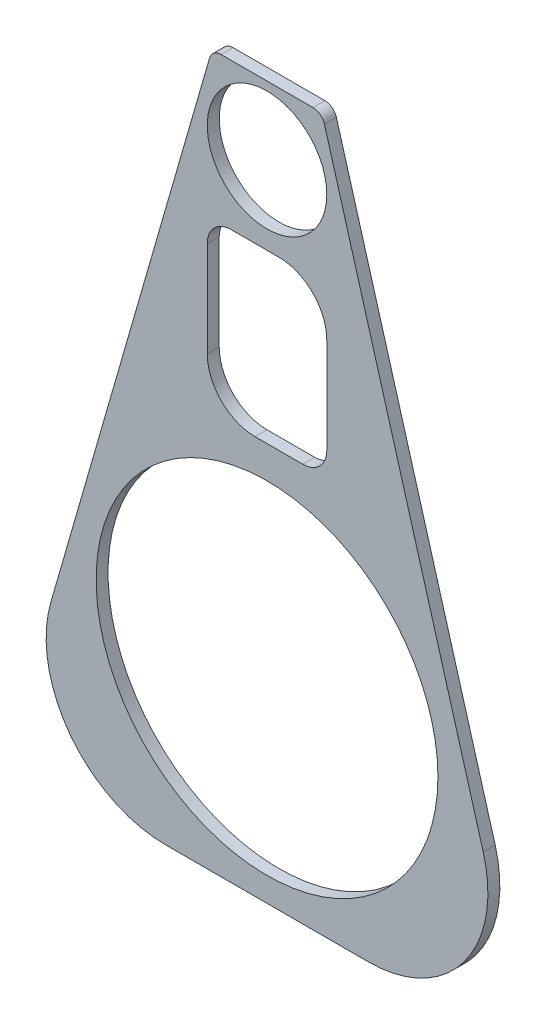
SolidWorks part; units mm, degrees
material "6061 Alloy"
ref_plane "Front" through (0, 0, 0) normal (0, 0, 1) x (1, 0, 0)
ref_plane "Top" through (0, 0, 0) normal (0, 1, 0) x (1, 0, 0)
ref_plane "Right" through (0, 0, 0) normal (1, 0, 0) x (0, 0, -1)
sketch "Sketch3" plane through (0, 0, 0) normal (0, 0, 1) x (1, 0, 0)
  line L1 (969.886, -1066.4574) -> (305.5143, 1238.3736)
  line L3 (-174.8832, 1238.3736) -> (-839.2549, -1066.4574)
  line L4 (65.3155, 1274.5248) -> (65.3155, -1694.2708) construction
  line L17 (-126.8393, 1274.5248) -> (257.4704, 1274.5248)
  line L19 (15.3155, -38.8919) -> (215.3155, -38.8919)
  line L20 (-184.6845, 161.1081) -> (-184.6845, 561.1081)
  line L21 (-84.6845, 661.1081) -> (115.3155, 661.1081)
  line L22 (315.3155, 61.1081) -> (315.3155, 461.1081)
  line L23 (-358.8163, -1704.9447) -> (489.4474, -1704.9447)
  line L24 (-184.6845, -38.8919) -> (315.3155, 661.1081) construction
  line L25 (-184.6845, 661.1081) -> (315.3155, -38.8919) construction
  arc A10 (-174.8832, 1238.3736) -> (-126.8393, 1274.5248) centre (-126.8393, 1224.5248) cw
  arc A11 (305.5143, 1238.3736) -> (257.4704, 1274.5248) centre (257.4704, 1224.5248) ccw
  circle A13 centre (65.3155, 988.5365) radius 250
  circle A14 centre (65.3155, -888.8919) radius 715
  arc A15 (-839.2549, -1066.4574) -> (-358.8163, -1704.9447) centre (-358.8163, -1204.9447) ccw
  arc A16 (489.4474, -1704.9447) -> (969.886, -1066.4574) centre (489.4474, -1204.9447) ccw
  arc A17 (-184.6845, 161.1081) -> (15.3155, -38.8919) centre (15.3155, 161.1081) ccw
  arc A18 (315.3155, 461.1081) -> (115.3155, 661.1081) centre (115.3155, 461.1081) ccw
  arc A19 (-184.6845, 561.1081) -> (-84.6845, 661.1081) centre (-84.6845, 561.1081) cw
  arc A20 (215.3155, -38.8919) -> (315.3155, 61.1081) centre (215.3155, 61.1081) ccw
  point P1 (65.3155, 311.1081)
  point P11 (60.2939, 331.5151)
  point P28 (-164.4625, 1274.5248)
  point P33 (295.0936, 1274.5248)
  dimension "D4" = 500
  dimension "D5" = 700
  dimension "D6" = 500
  dimension "D7" = 500
  dimension "D8" = 500
  dimension "D9" = 50
  dimension "D11" = 50
  dimension "D2" = 1430
  dimension "D10" = 200
  dimension "D12" = 200
  dimension "D13" = 100
  dimension "D14" = 100
  dimension "D3" = 1200
  dimension "D15" = 820
  dimension "D16" = 820
  dimension "D17" = 300
  dimension "D18" = 300
extrude "Boss-Extrude1" add sketch "Sketch3" along normal blind 50
